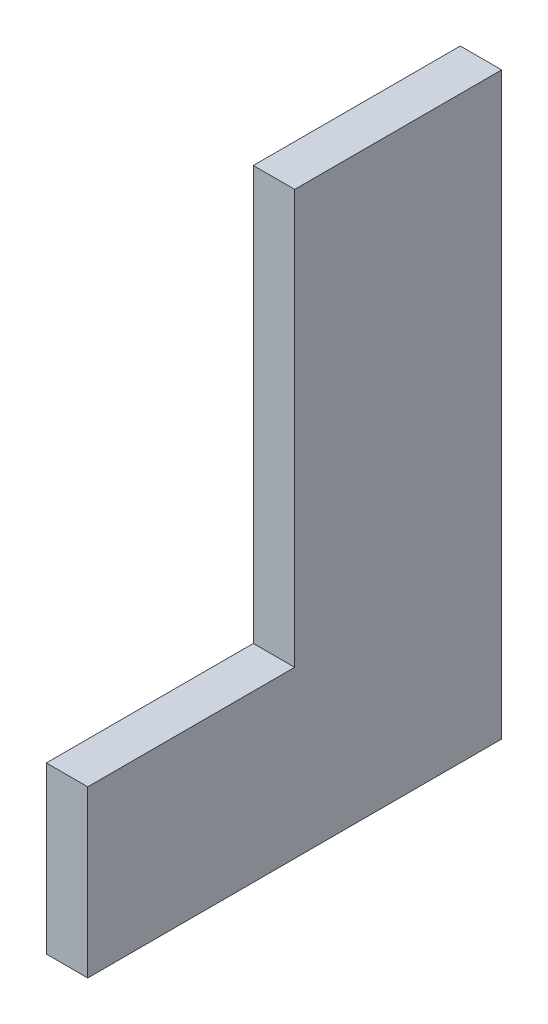
SolidWorks part; units mm, degrees
ref_plane "前视基准面" through (0, 0, 0) normal (0, 0, 1) x (1, 0, 0)
ref_plane "上视基准面" through (0, 0, 0) normal (0, 1, 0) x (1, 0, 0)
ref_plane "右视基准面" through (0, 0, 0) normal (1, 0, 0) x (0, 0, -1)
other "Configuration Table"
sketch "草图1" plane through (0, 0, 0) normal (0, 0, 1) x (1, 0, 0)
  line L9 (-10, -140) -> (10, -140)
  line L10 (-10, -140) -> (-10, 140)
  line L11 (-10, 140) -> (10, 140)
  line L12 (10, -140) -> (10, 140)
  line L13 (-10, -140) -> (10, 140) construction
  line L14 (-10, 140) -> (10, -140) construction
  point P0 (0, 0)
  dimension "D1" = 280
  dimension "D2" = 20
extrude "凸台-拉伸1" add sketch "草图1" along normal blind 100
sketch "草图2" plane through (-10, 0, 0) normal (-1, 0, 0) x (0, 0, 1)
  line L0 (100, -140) -> (0, -140) construction
  line L1 (200, -60) -> (100, -60)
  line L2 (200, -60) -> (200, -140)
  line L3 (200, -140) -> (100, -140)
  line L4 (100, -60) -> (100, -140)
  line L5 (100, 140) -> (100, -140) construction
extrude "凸台-拉伸2" add sketch "草图2" against normal up to surface (20 mm away) up to face at (10, 0, 50)
